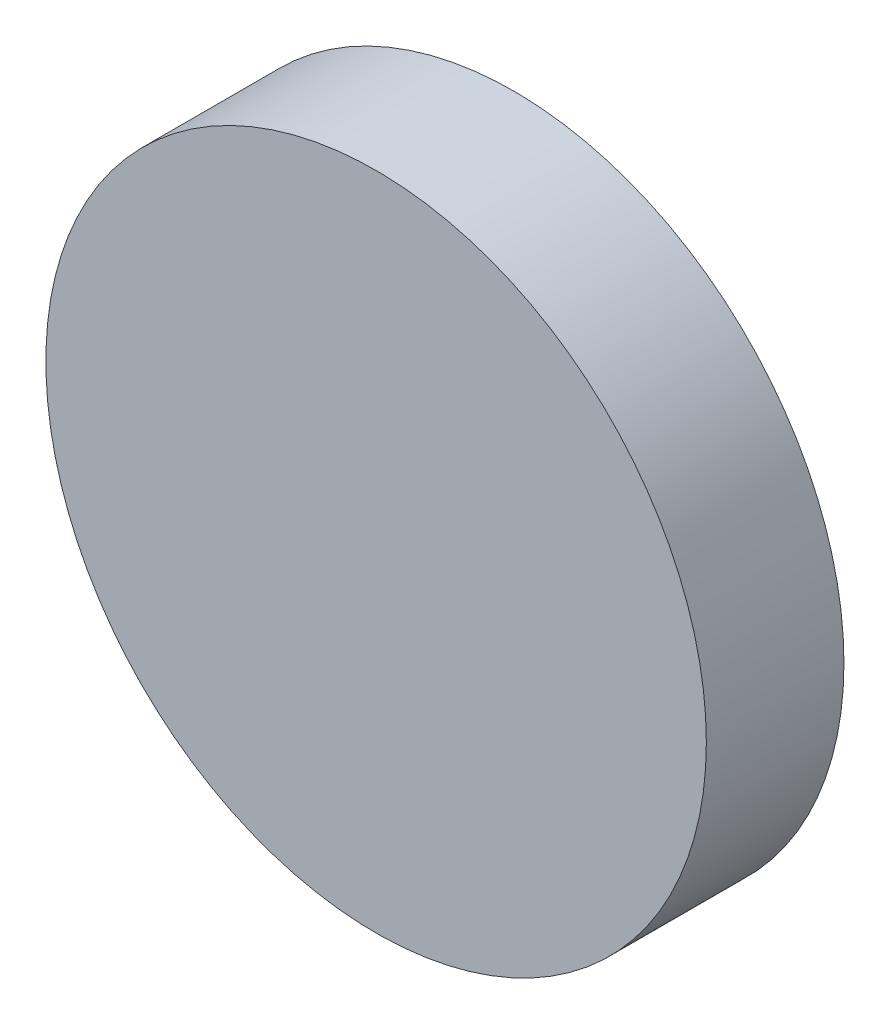
SolidWorks part; units mm, degrees
ref_plane "前视基准面" through (0, 0, 0) normal (0, 0, 1) x (1, 0, 0)
ref_plane "上视基准面" through (0, 0, 0) normal (0, 1, 0) x (1, 0, 0)
ref_plane "右视基准面" through (0, 0, 0) normal (1, 0, 0) x (0, 0, -1)
sketch "Sketch1" plane through (0, 0, 0) normal (0, 0, 1) x (1, 0, 0)
  circle A0 centre (0, 0) radius 24
  dimension "D1" = 48
extrude "Boss-Extrude1" add sketch "Sketch1" along normal blind 10
sketch "Sketch3" plane through (0, 0, 0) normal (0, 1, 0) x (1, 0, 0)
  line L0 (24, 0) -> (-24, 0) construction
  line L1 (18.8, 2) -> (18.8, -2)
  arc A0 (18.8, -2) -> (18.8, 2) centre (18.8, 0) ccw
  dimension "D1" = 4
  dimension "D2" = 18.8
revolve "Revolve1" add sketch "Sketch3" angle 360 about L1
pattern_circular "CirPattern1" count 11 over 360 about axis through (0, 0, 0) along (0, 0, 1) of "Revolve1"
sketch "Orientation Sketch" plane through (0, 0, 0) normal (0, 0, -1) x (-1, 0, 0)
  circle A0 centre (-15.8156, -10.164) radius 2 construction
  circle A1 centre (-7.8098, -17.1011) radius 2 construction
  circle A2 centre (2.6755, -18.6086) radius 2 construction
  circle A3 centre (12.3114, -14.2081) radius 2 construction
  circle A4 centre (18.0385, -5.2966) radius 2 construction
  circle A5 centre (18.0385, 5.2966) radius 2 construction
  circle A6 centre (12.3114, 14.2081) radius 2 construction
  circle A7 centre (2.6755, 18.6086) radius 2 construction
  circle A8 centre (-7.8098, 17.1011) radius 2 construction
  circle A9 centre (-15.8156, 10.164) radius 2 construction
  circle A10 centre (-18.8, 0) radius 2 construction
  circle A11 centre (0, 0) radius 24 construction
  circle A12 centre (-15.8156, -10.164) radius 2
  circle A13 centre (-7.8098, -17.1011) radius 2
  circle A14 centre (2.6755, -18.6086) radius 2
  circle A15 centre (12.3114, -14.2081) radius 2
  circle A16 centre (18.0385, -5.2966) radius 2
  circle A17 centre (18.0385, 5.2966) radius 2
  circle A18 centre (12.3114, 14.2081) radius 2
  circle A19 centre (2.6755, 18.6086) radius 2
  circle A20 centre (-7.8098, 17.1011) radius 2
  circle A21 centre (-15.8156, 10.164) radius 2
  circle A22 centre (-18.8, 0) radius 2
  circle A23 centre (0, 0) radius 24 construction
  point P36 (0, 0)
other "FormTool1"
